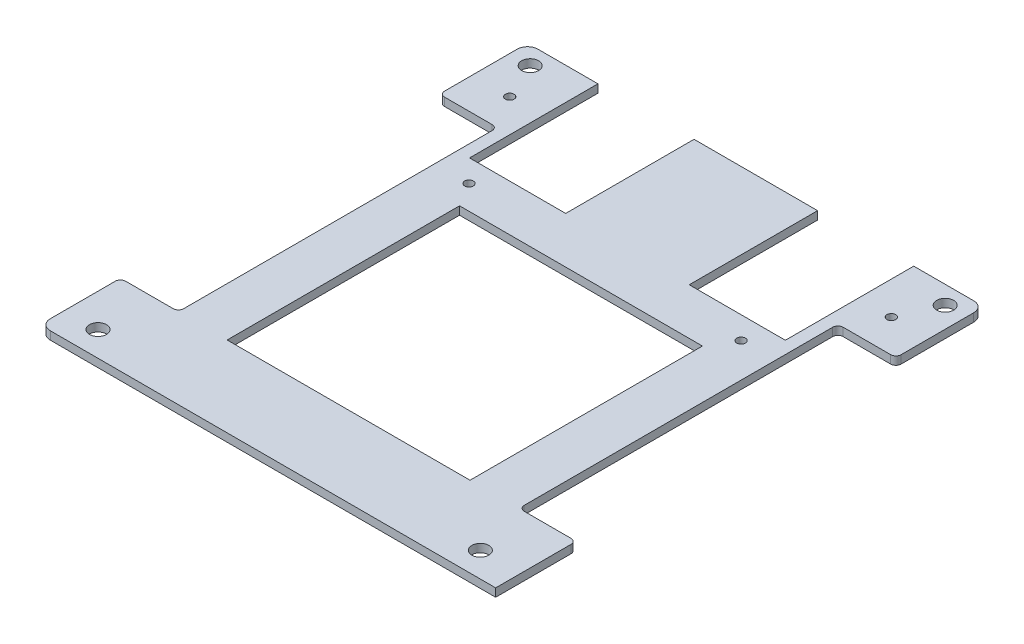
SolidWorks part; units mm, degrees
material "Copper"
ref_plane "Front Plane" through (0, 0, 0) normal (0, 0, 1) x (1, 0, 0)
ref_plane "Top Plane" through (0, 0, 0) normal (0, 1, 0) x (1, 0, 0)
ref_plane "Right Plane" through (0, 0, 0) normal (1, 0, 0) x (0, 0, -1)
sketch "Sketch1" plane through (0, 0, 0) normal (0, 1, 0) x (1, 0, 0)
  line L0 (-44, 45) -> (-44, 30.9986)
  line L1 (-43, 29.9986) -> (-33.824, 29.9986)
  line L2 (-42, 47) -> (42, 47)
  line L3 (44, 45) -> (44, 31.284)
  line L4 (32.824, 28.9986) -> (32.824, -30.4694)
  line L5 (26.22, 17.9319) -> (-33.6927, 17.9319) construction
  line L6 (33.824, 29.9986) -> (43, 29.9986)
  line L7 (43.8497, -38.27) -> (43.8497, -47)
  line L8 (42.7059, -47) -> (-42, -47)
  line L9 (-44, -45) -> (-44, -38.977)
  line L10 (-32.824, 28.9986) -> (-32.824, -30.4694)
  line L11 (33.824, -31.4694) -> (36.1, -31.4694)
  line L12 (23.409, -31.5) -> (-23.409, -31.5)
  line L13 (-23.409, -31.5) -> (-23.409, 13.2954)
  line L14 (-23.409, 13.2954) -> (-12.909, 13.2954)
  line L15 (-12.909, 13.2954) -> (-12.909, 25.9954)
  line L16 (-12.909, 25.9954) -> (12.909, 25.9954)
  line L17 (12.909, 25.9954) -> (12.909, 13.2954)
  line L18 (12.909, 13.2954) -> (23.409, 13.2954)
  line L19 (23.409, 13.2954) -> (23.409, -31.5)
  line L20 (43.8497, -38.27) -> (43.8497, -32.4694)
  line L21 (42.8497, -31.4694) -> (36.1, -31.4694)
  line L22 (43.8497, -47) -> (42.7059, -47)
  line L23 (-44, 29.9986) -> (52.9697, 29.9986) construction
  line L24 (44, 31.284) -> (44, 30.9986)
  line L25 (-33.824, -31.4694) -> (-36.1, -31.4694)
  line L26 (-44, -38.977) -> (-44, -32.4694)
  line L27 (-43, -31.4694) -> (-36.1, -31.4694)
  circle A0 centre (40, 43.5) radius 1.6383
  circle A1 centre (-40, 43.5) radius 1.6383
  circle A2 centre (-37.6, -42.2) radius 1.6383
  circle A3 centre (36.1, -42.2) radius 1.6383
  arc A4 (32.824, -30.4694) -> (33.824, -31.4694) centre (33.824, -30.4694) ccw
  arc A5 (-42, 47) -> (-44, 45) centre (-42, 45) ccw
  arc A6 (44, 45) -> (42, 47) centre (42, 45) ccw
  arc A7 (-32.824, -30.4694) -> (-33.824, -31.4694) centre (-33.824, -30.4694) cw
  circle A8 centre (26.22, 17.9319) radius 0.8382
  circle A9 centre (-26.22, 17.9319) radius 0.8382
  arc A10 (-33.824, 29.9986) -> (-32.824, 28.9986) centre (-33.824, 28.9986) cw
  arc A11 (-44, -45) -> (-42, -47) centre (-42, -45) ccw
  arc A12 (-44, 30.9986) -> (-43, 29.9986) centre (-43, 30.9986) ccw
  arc A13 (44, 30.9986) -> (43, 29.9986) centre (43, 30.9986) cw
  arc A14 (43.8497, -32.4694) -> (42.8497, -31.4694) centre (42.8497, -32.4694) ccw
  arc A15 (-44, -32.4694) -> (-43, -31.4694) centre (-43, -32.4694) cw
  arc A16 (33.824, 29.9986) -> (32.824, 28.9986) centre (33.824, 28.9986) ccw
  point P27 (32.824, -31.4694)
  point P51 (-32.824, -31.4694)
  point P54 (-32.824, 29.9986)
  point P60 (44, 29.9986)
  point P67 (32.824, 29.9986)
  dimension "D24" = 61.468
  dimension "D3" = 80
  dimension "D25" = 1.6764
  dimension "D27" = 1.6764
  dimension "D8" = 1
  dimension "D22" = 1
  dimension "D2" = 6.4
  dimension "D4" = 44.7954
  dimension "D5" = 12.7
  dimension "D6" = 44.7954
  dimension "D7" = 3.5
  dimension "D9" = 4
  dimension "D10" = 3.5
  dimension "D11" = 85.7
  dimension "D12" = 85.7
  dimension "D13" = 21.0046
  dimension "D14" = 11.176
  dimension "D15" = 84
  dimension "D16" = 25.818
  dimension "D17" = 12.7
  dimension "D18" = 46.818
  dimension "D19" = 10.5
  dimension "D20" = 10.5
  dimension "D21" = 73.7
  dimension "D23" = 13.716
  dimension "D26" = 6.604
  dimension "D28" = 6.604
  dimension "D29" = 11.176
  dimension "D30" = 61.468
  dimension "D31" = 3.276
  dimension "D32" = 3.276
extrude "Boss-Extrude1" add sketch "Sketch1" along normal blind 1.575
sketch "Sketch2" plane through (0, 1.575, 0) normal (0, 1, 0) x (1, 0, 0)
  line L0 (-12.909, 19.06) -> (-30.435, 19.06)
  line L1 (42, 47) -> (-42, 47) construction
  line L2 (-12.909, 25.9954) -> (12.909, 25.9954) construction
  line L3 (-30.435, 47) -> (30.435, 47)
  line L4 (12.909, 13.2954) -> (12.909, 25.9954) construction
  line L5 (12.909, 19.06) -> (30.435, 19.06)
  line L6 (30.435, 19.06) -> (30.435, 47)
  line L7 (0, 47) -> (0, -47) construction
  line L8 (-42, -47) -> (43.8497, -47) construction
  line L9 (-12.909, 25.9954) -> (-12.909, 19.06)
  line L10 (-30.435, 19.06) -> (-30.435, 47)
  line L11 (12.909, 25.9954) -> (12.909, 19.06)
  line L13 (-12.909, 25.9954) -> (12.909, 25.9954)
  dimension "D1" = 27.94
  dimension "D2" = 17.526
extrude "Cut-Extrude1" cut sketch "Sketch2" against normal blind 2.54
sketch "Sketch15" plane through (0, 1.575, 0) normal (0, 1, 0) x (1, 0, 0)
  line L0 (-30.435, 47) -> (-30.435, 19.06) construction
  line L4 (42, 47) -> (30.435, 47) construction
  line L5 (30.435, 19.06) -> (30.435, 47) construction
  circle A0 centre (-36.785, 36.35) radius 0.8382
  circle A1 centre (36.785, 36.332) radius 0.8382
  dimension "D1" = 1.6764
  dimension "D3" = 1.6764
  dimension "D4" = 10.668
  dimension "D2" = 6.35
  dimension "D5" = 6.35
extrude "Cut-Extrude5" cut sketch "Sketch15" against normal blind 1.575
sketch "Sketch16" plane through (0, 1.575, 0) normal (0, 1, 0) x (1, 0, 0)
  line L1 (12.909, 19.06) -> (12.909, 13.2954)
  line L2 (12.909, 13.2954) -> (-12.909, 13.2954)
  line L3 (-11.909, 47) -> (-11.909, 22.2554)
  line L4 (-30.435, 22.2554) -> (-11.909, 22.2554)
  line L5 (11.909, 22.2554) -> (11.909, 47)
  line L6 (11.909, 47) -> (-11.909, 47)
  line L7 (-30.435, 47) -> (-30.435, 19.06) construction
  line L9 (-12.909, 19.06) -> (-12.909, 13.2954)
  line L10 (-30.435, 47) -> (-42, 47) construction
  line L11 (11.909, 22.2554) -> (30.435, 22.2554)
  line L12 (30.435, 19.06) -> (30.435, 47) construction
  line L13 (30.435, 22.2554) -> (30.435, 19.06)
  line L14 (30.435, 19.06) -> (12.909, 19.06)
  line L15 (-30.435, 22.2554) -> (-30.435, 19.06)
  line L16 (-30.435, 19.06) -> (-12.909, 19.06)
  dimension "D1" = 24.7446
extrude "Boss-Extrude2" add sketch "Sketch16" against normal blind 1.575
